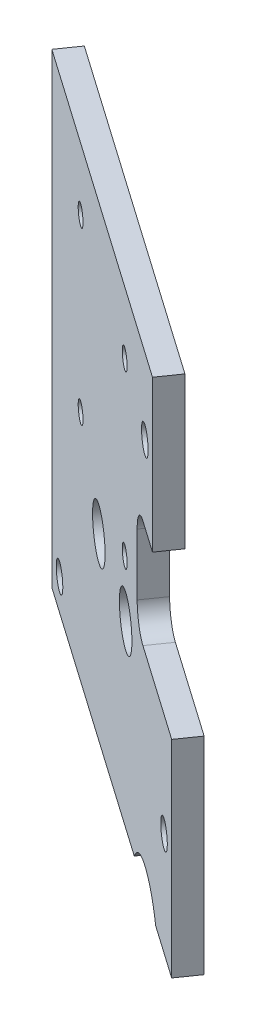
SolidWorks part; units mm, degrees
ref_plane "Front Plane" through (0, 0, 0) normal (0, 0, 1) x (1, 0, 0)
ref_plane "Top Plane" through (0, 0, 0) normal (0, 1, 0) x (1, 0, 0)
ref_plane "Right Plane" through (0, 0, 0) normal (1, 0, 0) x (0, 0, -1)
sketch "Sketch1" plane through (14.78, 0, -21.1463) normal (0.5729, 0, -0.8196) x (-0.8196, 0, -0.5729)
  line L0 (13.8934, 266.5116) -> (18.8934, 266.5116)
  line L1 (13.8934, 286.0116) -> (66.3934, 286.0116)
  line L2 (13.8934, 286.0116) -> (13.8934, 266.5116)
  line L3 (23.3978, 226.0116) -> (66.3934, 226.0116)
  line L4 (66.3934, 286.0116) -> (66.3934, 226.0116)
  line L6 (12.2111, 226.0116) -> (3.8793, 226.0116)
  line L8 (3.8793, 226.0116) -> (3.8793, 252.6116)
  line L9 (3.8793, 252.6116) -> (18.8934, 252.6116)
  line L10 (21.8934, 255.6116) -> (21.8934, 263.5116)
  line L11 (13.8934, 276.2616) -> (66.3934, 276.2616) construction
  line L12 (3.8793, 239.3116) -> (66.3934, 239.3116) construction
  circle A3 centre (27.8934, 249.0616) radius 3.25
  circle A5 centre (41.8934, 249.0616) radius 3.25
  circle A6 centre (62.3934, 230.0116) radius 1.25 construction
  circle A8 centre (17.8934, 276.2616) radius 1.25 construction
  arc A9 (18.8934, 252.6116) -> (21.8934, 255.6116) centre (18.8934, 255.6116) ccw
  arc A10 (21.8934, 263.5116) -> (18.8934, 266.5116) centre (18.8934, 263.5116) ccw
  circle A11 centre (7.8793, 239.3116) radius 1.25 construction
  arc A13 (23.3978, 226.0116) -> (12.2111, 226.0116) centre (17.8045, 221.8027) ccw
  dimension "D3" = 6.5
  dimension "D4" = 3
  dimension "D5" = 6.5
  dimension "D6" = 2.5
  dimension "D7" = 2.5
  dimension "D8" = 60
  dimension "D9" = 2.5
  dimension "D21" = 24.5
  dimension "D22" = 38.5
  dimension "D23" = 23.05
  dimension "D24" = 23.05
  dimension "D1" = 19.5
  dimension "D10" = 26.6
  dimension "D11" = 5
  dimension "D12" = 13.9
  dimension "D13" = 4
  dimension "D14" = 44.5
  dimension "D15" = 7.9
  dimension "D16" = 4
  dimension "D17" = 4
  dimension "D18" = 4
  dimension "D19" = 8.3318
  dimension "D20" = 42.9956
extrude "Boss-Extrude1" add sketch "Sketch1" along normal blind 3
sketch "Sketch7" plane through (16.4987, 0, -23.6052) normal (0.5729, 0, -0.8196) x (-0.8196, 0, -0.5729)
  line L0 (66.3934, 286.0116) -> (13.8934, 286.0116) construction
  line L1 (28.3934, 278.0116) -> (51.3934, 278.0116) construction
  line L2 (28.3934, 278.0116) -> (28.3934, 256.0116) construction
  line L3 (28.3934, 256.0116) -> (51.3934, 256.0116) construction
  line L4 (51.3934, 278.0116) -> (51.3934, 256.0116) construction
  line L6 (66.3934, 226.0116) -> (66.3934, 286.0116) construction
  circle A0 centre (28.3934, 278.0116) radius 1.25
  circle A1 centre (51.3934, 278.0116) radius 1.25
  circle A2 centre (28.3934, 256.0116) radius 1.25
  circle A3 centre (51.3934, 256.0116) radius 1.25
  point P12 (51.3934, 267.0116)
  dimension "D5" = 2.5
  dimension "D6" = 2.5
  dimension "D7" = 2.5
  dimension "D8" = 2.5
  dimension "D1" = 23
  dimension "D2" = 22
  dimension "D3" = 8
  dimension "D4" = 15
extrude "Cut-Extrude1" cut sketch "Sketch7" against normal blind 3
hole_wizard "CSK for M3 Hex Socket Countersunk Head Screw2" positions "Sketch9" profile "Sketch11" countersink size "M3" standard "DIN"
sketch "Sketch9" plane through (16.4987, 0, -23.6052) normal (0.5729, 0, -0.8196) x (-0.8196, 0, -0.5729)
  point P0 (17.8934, 276.2616)
  point P3 (7.8793, 239.3116)
  point P6 (62.3934, 230.0116)
sketch "Sketch11" plane through (1.8325, 276.2616, -33.856) normal (0, 1, 0) x (-0.8196, 0, -0.5729)
  line L0 (0, 0) -> (0, 4.0215)
  line L1 (0, 4.0215) -> (1.7, 3)
  line L2 (1.7, 3) -> (1.7, 1.77)
  line L3 (1.7, 1.77) -> (3.47, 0)
  line L5 (3.47, 0) -> (0, 0)
  line L6 (-1.7, 1.77) -> (-3.47, 0) construction
  line L10 (0, 4.0215) -> (-1.7, 3) construction
  line L11 (0, -6.35) -> (0, 107.95) construction
  dimension "Диаметр отверстия" = 3.4
  dimension "Глубина отверстия" = 3
  dimension "Диаметр передней зенковки" = 6.94
  dimension "Угол передней зенковки" = 90
  dimension "Угол заточки сверла" = 118
